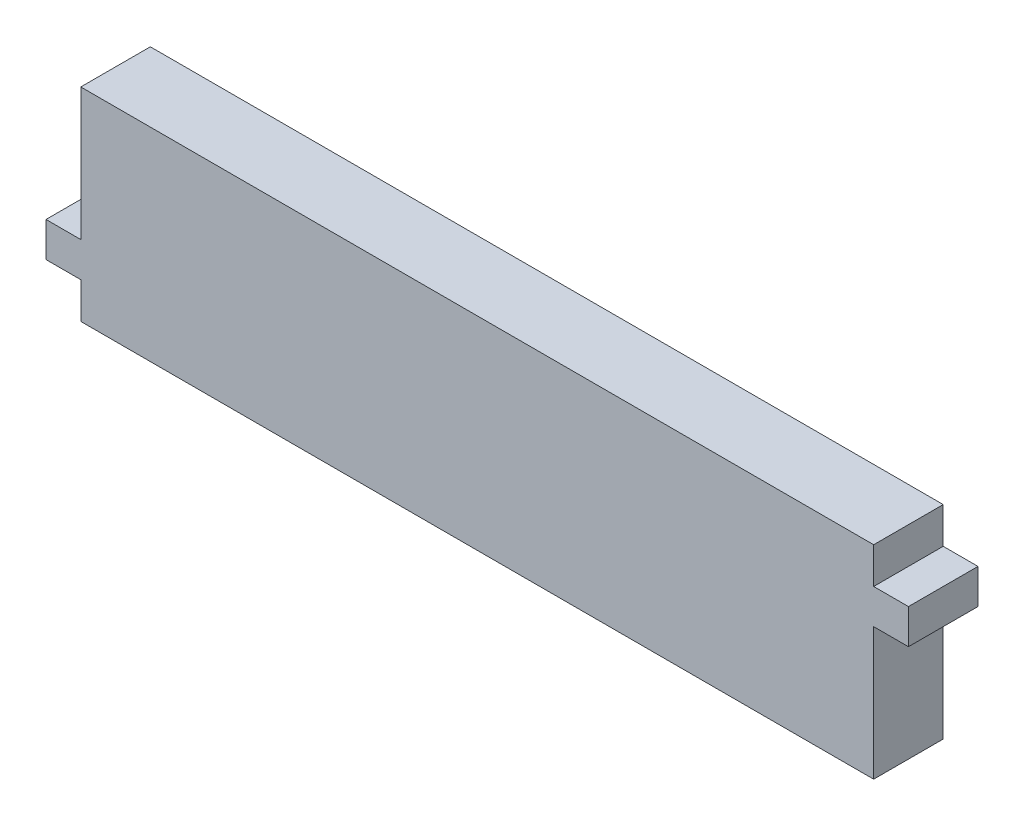
SolidWorks part; units mm, degrees
material "Balsa"
ref_plane "Front Plane" through (0, 0, 0) normal (0, 0, 1) x (1, 0, 0)
ref_plane "Top Plane" through (0, 0, 0) normal (0, 1, 0) x (1, 0, 0)
ref_plane "Right Plane" through (0, 0, 0) normal (1, 0, 0) x (0, 0, -1)
sketch "Sketch4" plane through (0, 0, 0) normal (0, 0, 1) x (1, 0, 0)
  line L0 (129.1138, -14.4853) -> (132.2888, -14.4853)
  line L1 (132.2888, -14.4853) -> (132.2888, -17.6603)
  line L2 (132.2888, -17.6603) -> (129.1138, -17.6603)
  line L3 (129.1138, -17.6603) -> (129.1138, -23.2483)
  line L4 (129.1138, -23.2483) -> (129.1138, -26.4233)
  line L5 (129.1138, -9.6871) -> (129.1138, -33.2002) construction
  line L6 (56.7238, -23.2483) -> (53.5488, -23.2483)
  line L7 (53.5488, -23.2483) -> (53.5488, -26.4233)
  line L8 (53.5488, -26.4233) -> (56.7238, -26.4233)
  line L9 (56.7238, -26.4233) -> (56.7238, -29.7253)
  line L10 (56.7238, -29.7253) -> (129.1138, -29.7253)
  line L11 (129.1138, -29.7253) -> (129.1138, -26.4233)
  line L12 (129.1138, -14.4853) -> (129.1138, -11.1833)
  line L13 (56.7238, -23.2483) -> (56.7238, -11.1833)
  line L14 (56.7238, -11.1833) -> (129.1138, -11.1833)
  point P14 (129.1138, -20.4543)
  point P15 (129.1138, -11.1833)
  point P16 (129.1138, -29.7253)
  dimension "D1" = 9.271
  dimension "D2" = 9.271
extrude "Boss-Extrude1" add sketch "Sketch4" along normal up to surface (6.35 mm away)
